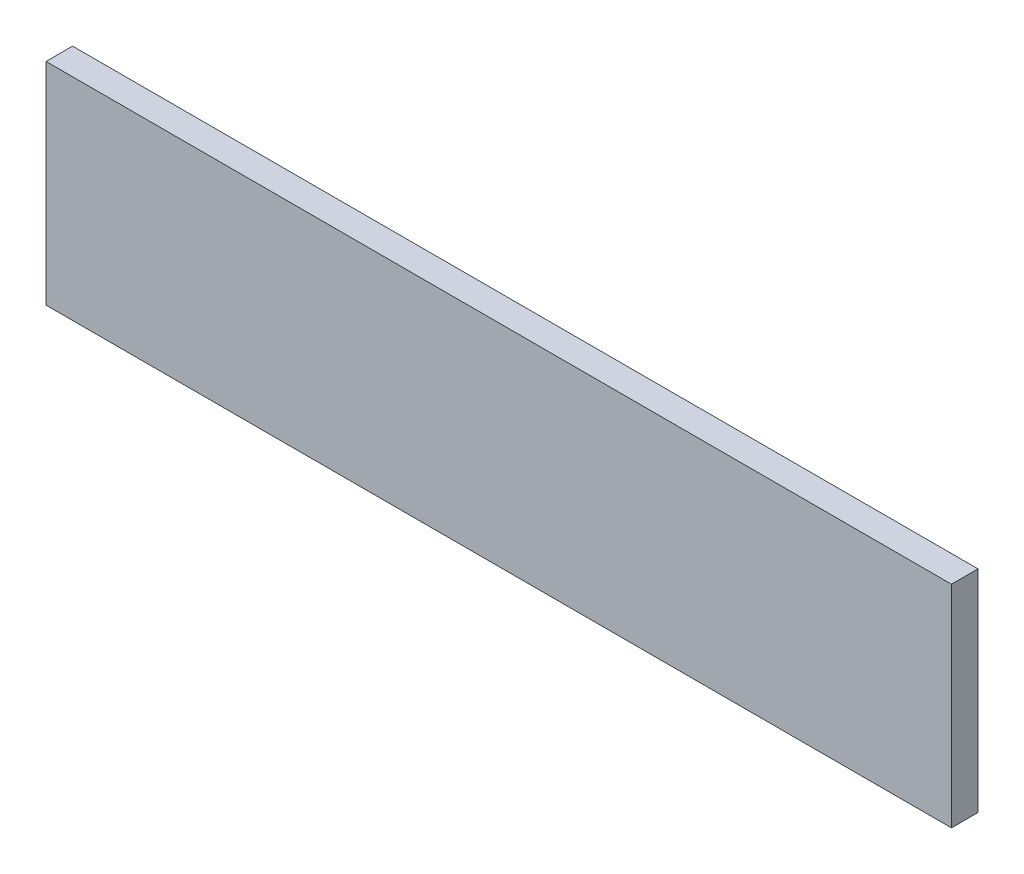
SolidWorks part; units mm, degrees
ref_plane "Front Plane" through (0, 0, 0) normal (0, 0, 1) x (1, 0, 0)
ref_plane "Top Plane" through (0, 0, 0) normal (0, 1, 0) x (1, 0, 0)
ref_plane "Right Plane" through (0, 0, 0) normal (1, 0, 0) x (0, 0, -1)
sketch "Sketch1" plane through (0, 0, 0) normal (1, 0, 0) x (0, 0, -1)
  line L1 (-1.95, 15.5) -> (1.95, 15.5)
  line L2 (-1.95, 15.5) -> (-1.95, -15.5)
  line L3 (-1.95, -15.5) -> (1.95, -15.5)
  line L4 (1.95, 15.5) -> (1.95, -15.5)
  line L5 (-1.95, 15.5) -> (1.95, -15.5) construction
  line L6 (-1.95, -15.5) -> (1.95, 15.5) construction
  point P0 (0, 0)
  dimension "D1" = 31
  dimension "D2" = 3.9
extrude "Boss-Extrude1" add sketch "Sketch1" along normal blind 133
